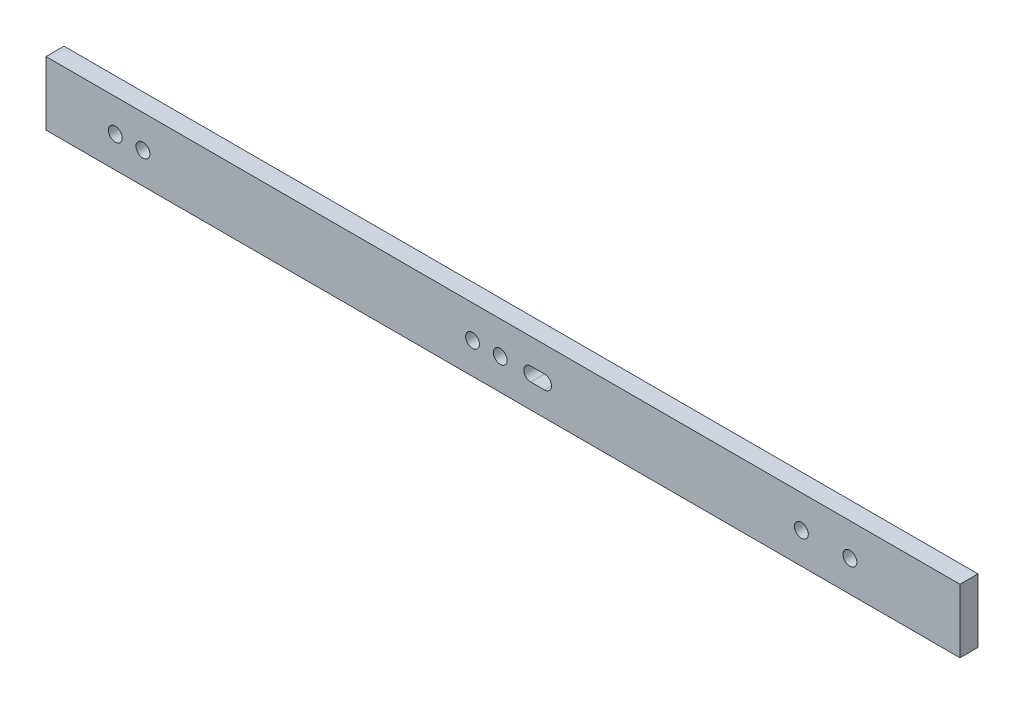
SolidWorks part; units mm, degrees
ref_plane "Спереди" through (0, 0, 0) normal (0, 0, 1) x (1, 0, 0)
ref_plane "Сверху" through (0, 0, 0) normal (0, 1, 0) x (1, 0, 0)
ref_plane "Справа" through (0, 0, 0) normal (1, 0, 0) x (0, 0, -1)
ref_plane "Плоскость4" through (0, 0, 6.5) normal (0, 0, 1) x (1, 0, 0)
sketch "Эскиз1" plane through (0, 0, 6.5) normal (0, 0, 1) x (1, 0, 0)
  line L0 (180, 8.75) -> (175, 8.75)
  line L1 (175, 13.75) -> (180, 13.75)
  line L2 (330, 23) -> (0, 23)
  line L3 (0, 23) -> (0, 0)
  line L4 (0, 0) -> (330, 0)
  line L5 (330, 0) -> (330, 23)
  circle A0 centre (35, 11.25) radius 2.5
  circle A1 centre (25, 11.25) radius 2.5
  circle A2 centre (164, 11.25) radius 2.5
  circle A3 centre (154, 11.25) radius 2.5
  arc A4 (180, 13.75) -> (180, 8.75) centre (180, 11.25) cw
  arc A5 (175, 8.75) -> (175, 13.75) centre (175, 11.25) cw
  circle A6 centre (272.7221, 11.25) radius 2.5
  circle A7 centre (290.2502, 11.25) radius 2.5
extrude "Бобышка-Вытянуть1" add sketch "Эскиз1" against normal blind 6.5
